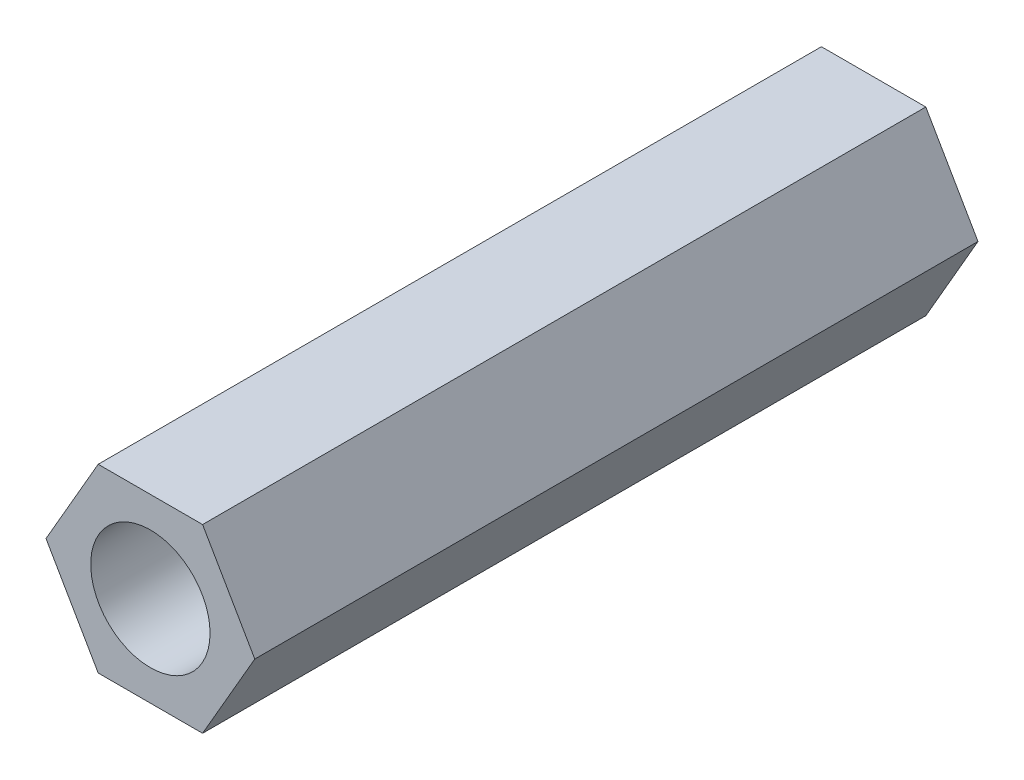
SolidWorks part; units mm, degrees
ref_plane "前视基准面" through (0, 0, 0) normal (0, 0, 1) x (1, 0, 0)
ref_plane "上视基准面" through (0, 0, 0) normal (0, 1, 0) x (1, 0, 0)
ref_plane "右视基准面" through (0, 0, 0) normal (1, 0, 0) x (0, 0, -1)
other "Configuration Table"
sketch "草图1" plane through (0, 0, 0) normal (0, 0, 1) x (1, 0, 0)
  line L6 (2.8868, 0) -> (1.4434, 2.5)
  line L7 (1.4434, 2.5) -> (-1.4434, 2.5)
  line L8 (-1.4434, 2.5) -> (-2.8868, 0)
  line L9 (-2.8868, 0) -> (-1.4434, -2.5)
  line L10 (-1.4434, -2.5) -> (1.4434, -2.5)
  line L11 (1.4434, -2.5) -> (2.8868, 0)
  circle A1 centre (0, 0) radius 1.65
extrude "20mm铝柱_M3通孔_D3p3" add sketch "草图1" along normal blind 20
